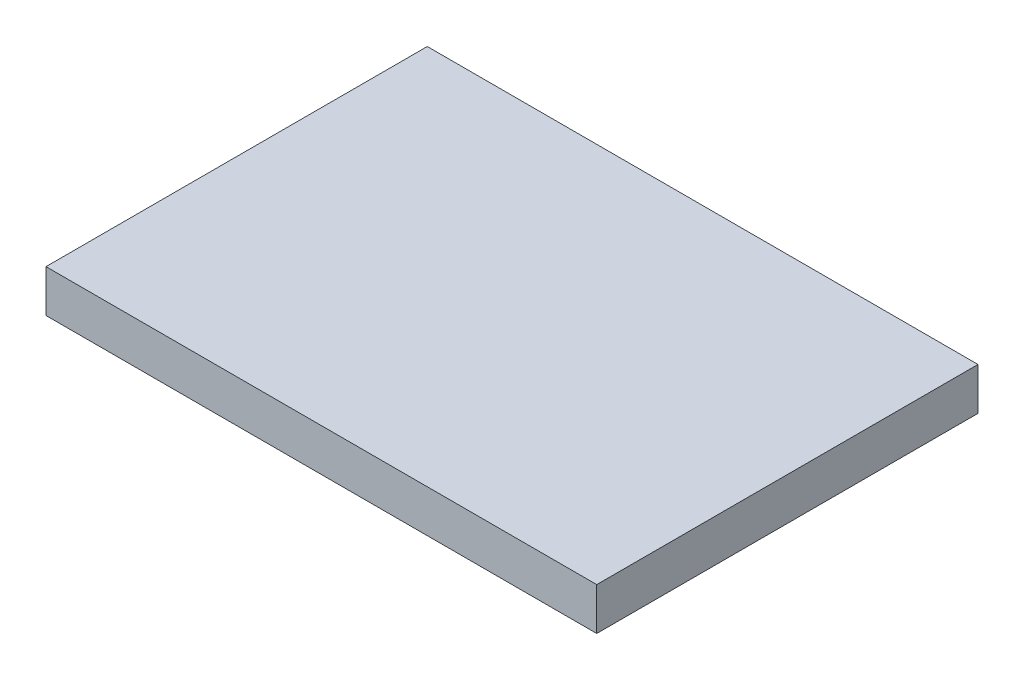
SolidWorks part; units mm, degrees
material "Custom Plastic"
ref_plane "Front Plane" through (0, 0, 0) normal (0, 0, 1) x (1, 0, 0)
ref_plane "Top Plane" through (0, 0, 0) normal (0, 1, 0) x (1, 0, 0)
ref_plane "Right Plane" through (0, 0, 0) normal (1, 0, 0) x (0, 0, -1)
sketch "Sketch1" plane through (0, 0, 0) normal (0, 1, 0) x (1, 0, 0)
  line L1 (0, 0) -> (650, 0)
  line L2 (0, 0) -> (0, 450)
  line L3 (0, 450) -> (650, 450)
  line L4 (650, 0) -> (650, 450)
  dimension "D1" = 650
  dimension "D2" = 450
extrude "BATTERY" add sketch "Sketch1" along normal blind 50
